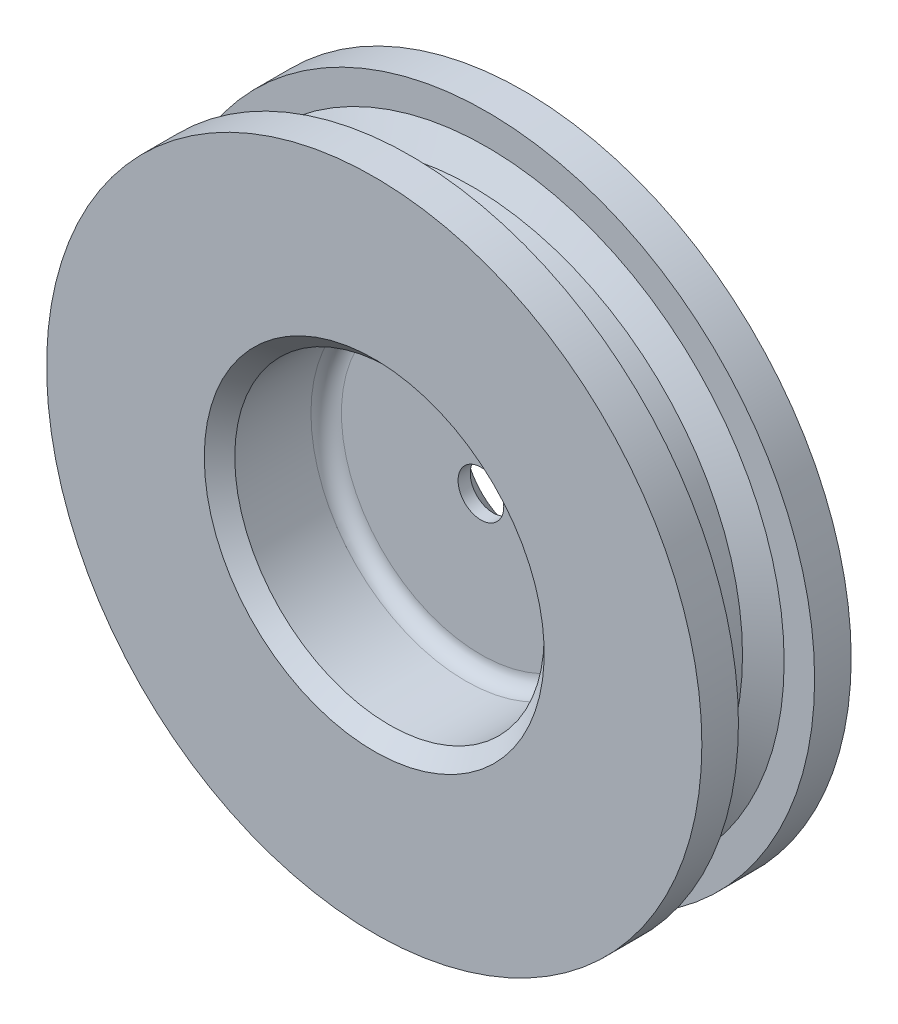
SolidWorks part; units mm, degrees
ref_plane "Plano frontal" through (0, 0, 0) normal (0, 0, 1) x (1, 0, 0)
ref_plane "Plano superior" through (0, 0, 0) normal (0, 1, 0) x (1, 0, 0)
ref_plane "Plano direito" through (0, 0, 0) normal (1, 0, 0) x (0, 0, -1)
sketch "Esboço4" plane through (0, 0, 0) normal (1, 0, 0) x (0, 0, -1)
  line L0 (-4.9, 0) -> (-4.9, 20)
  line L1 (-4.9, 20) -> (-2.5, 20)
  line L2 (-2.5, 20) -> (-2.5, 18)
  line L3 (-2.5, 18) -> (-1.5, 16.2679)
  line L4 (-1.5, 16.2679) -> (0, 16.2679)
  line L9 (4.9, 0) -> (-4.9, 0)
  line L10 (0, 0) -> (0, 20) construction
  line L11 (1.5, 16.2679) -> (0, 16.2679)
  line L12 (2.5, 18) -> (1.5, 16.2679)
  line L13 (2.5, 20) -> (2.5, 18)
  line L14 (4.9, 20) -> (2.5, 20)
  line L15 (4.9, 0) -> (4.9, 20)
  line L16 (-9.0583, -1.5) -> (6.4263, -1.5) construction
  point P2 (-0.75, 16.2679)
  point P17 (-1.316, -1.5)
  dimension "D1" = 20
  dimension "D2" = 2.4
  dimension "D3" = 2
  dimension "D4" = 60
  dimension "D5" = 1.5
  dimension "D6" = 2.5
  dimension "D7" = 16.2679
  dimension "D8" = 1.5
revolve "Revolução1" add sketch "Esboço4" angle 360 about L16
sketch "Esboço5" plane through (0, 0, 4.9) normal (0, 0, 1) x (1, 0, 0)
  circle A0 centre (0, -1.5) radius 10.1539
extrude "Corte-extrusão1" cut sketch "Esboço5" against normal blind 7
chamfer "Chanfro1" distance 1 angle 45 1 edges at (10.1539, -1.5, 4.9)
fillet "Filete1" radius 1 1 edges at (10.1539, -1.5, -2.1)
chamfer "Chanfro2" distance 2 angle 50 1 edges at (1.5, -1.5, -4.9)
